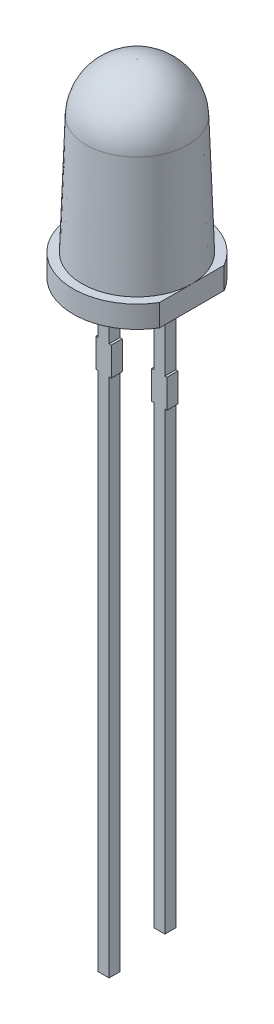
SolidWorks part; units mm, degrees
ref_plane "Front Plane" through (0, 0, 0) normal (0, 0, 1) x (1, 0, 0)
ref_plane "Top Plane" through (0, 0, 0) normal (0, 1, 0) x (1, 0, 0)
ref_plane "Right Plane" through (0, 0, 0) normal (1, 0, 0) x (0, 0, -1)
sketch "Sketch4" plane through (0, 0, 0) normal (0, 1, 0) x (1, 0, 0)
  line L0 (2.9743, 0) -> (-3.696, 0) construction
  line L2 (-1.52, 0.25) -> (-1.02, 0.25)
  line L3 (-1.52, 0.25) -> (-1.52, -0.25)
  line L4 (-1.52, -0.25) -> (-1.02, -0.25)
  line L5 (-1.02, 0.25) -> (-1.02, -0.25)
  line L6 (-1.52, 0.25) -> (-1.02, -0.25) construction
  line L7 (-1.52, -0.25) -> (-1.02, 0.25) construction
  line L8 (1.02, 0.25) -> (1.52, 0.25)
  line L9 (1.02, 0.25) -> (1.02, -0.25)
  line L10 (1.02, -0.25) -> (1.52, -0.25)
  line L11 (1.52, 0.25) -> (1.52, -0.25)
  line L12 (1.02, 0.25) -> (1.52, -0.25) construction
  line L13 (1.02, -0.25) -> (1.52, 0.25) construction
  point P3 (-1.27, 0)
  point P8 (1.27, 0)
  dimension "D1" = 0.5
  dimension "D2" = 0.5
  dimension "D3" = 0.5
  dimension "D4" = 0.5
  dimension "D5" = 1.27
  dimension "D6" = 1.27
extrude "Boss-Extrude3" add sketch "Sketch4" along normal blind 3.5 and the other way blind 25 separate body
sketch "Sketch5" plane through (0, 0, 0.25) normal (0, 0, 1) x (1, 0, 0)
  line L0 (-1.02, 3.3269) -> (-0.3288, 2.4555)
  line L2 (-1.02, -25) -> (-1.02, 3.5) construction
  line L3 (-0.3288, 2.4555) -> (-0.3288, 2.1844)
  line L4 (-0.3288, 2.1844) -> (-1.02, 2.1844)
  line L5 (-1.02, 2.1844) -> (-1.02, 3.3269)
  line L6 (1.02, 3.399) -> (-0.7949, 3.399)
  line L7 (1.02, -25) -> (1.02, 3.5) construction
  line L8 (-0.7949, 3.399) -> (0.1685, 2.1844)
  line L9 (0.1685, 2.1844) -> (1.02, 2.1844)
  line L10 (1.02, 2.1844) -> (1.02, 3.399)
extrude "Boss-Extrude4" add sketch "Sketch5" against normal blind 0.5
sketch "Sketch7" plane through (0, 3.399, 0) normal (0, 1, 0) x (1, 0, 0)
  line L0 (-0.538, 0) -> (0.9252, 0)
  arc A0 (-0.538, 0) -> (0.9252, 0) centre (0.1936, 0) ccw
revolve "Revolve1" add sketch "Sketch7" angle 180 about L0
sketch "Sketch8" plane through (0, 3.399, 0) normal (0, 1, 0) x (1, 0, 0)
  line L0 (-0.4407, 0) -> (0.8303, 0)
  arc A0 (-0.4407, 0) -> (0.8303, 0) centre (0.1948, 0.0036) ccw
revolve "Cut-Revolve1" cut sketch "Sketch8" angle 360 about L0
sketch "Sketch9" plane through (0, 3.5, 0) normal (0, 1, 0) x (1, 0, 0)
  circle A0 centre (-1.3038, 0) radius 0.02
ref_plane "Plane1" through (0, 2.9, 0) normal (0, 1, 0) x (1, 0, 0)
sketch "Sketch10" plane through (0, 2.9, 0) normal (0, 1, 0) x (1, 0, 0)
  line L1 (-0.1178, 0.3117) -> (0.4822, 0.3117)
  line L2 (-0.1178, 0.3117) -> (-0.1178, -0.2883)
  line L3 (-0.1178, -0.2883) -> (0.4822, -0.2883)
  line L4 (0.4822, 0.3117) -> (0.4822, -0.2883)
  line L5 (-0.1178, 0.3117) -> (0.4822, -0.2883) construction
  line L6 (-0.1178, -0.2883) -> (0.4822, 0.3117) construction
  arc A0 (0.8303, 0) -> (-0.4407, 0) centre (0.1948, -0.0036) ccw construction
  point P0 (0.1822, 0.0117)
  dimension "D1" = 0.6
  dimension "D2" = 0.6
extrude "Boss-Extrude5" add sketch "Sketch10" along normal blind 0.2
sketch "Sketch11" plane through (0, 3.1, 0) normal (0, 1, 0) x (1, 0, 0)
  line L1 (0.0731, 0.0871) -> (0.2767, 0.0871)
  line L2 (0.0731, 0.0871) -> (0.0731, -0.0871)
  line L3 (0.0731, -0.0871) -> (0.2767, -0.0871)
  line L4 (0.2767, 0.0871) -> (0.2767, -0.0871)
  line L5 (0.0731, 0.0871) -> (0.2767, -0.0871) construction
  line L6 (0.0731, -0.0871) -> (0.2767, 0.0871) construction
  point P0 (0.1749, 0)
extrude "Boss-Extrude6" add sketch "Sketch11" along normal blind 0.05
sketch3d "3DSketch1"
  spline S0 degree 3 poles (-1.3038, 3.5, 0) (-1.3325, 3.672, 0) (-0.9418, 3.891, 0) (-0.1244, 3.8563, 0) (0.1242, 3.692, 0) (0.2258, 3.5852, 0) (0.1729, 3.1438, 0) knots 0 0 0 0 0.135885 0.523149 0.614401 1 1 1 1
sweep "Sweep1" add profiles "Sketch9" path "3DSketch1"
fillet "Fillet2" radius 0.02 10 edges at (0.1749, 3.15, 0.0871) (0.0731, 3.15, 0) (0.1749, 3.15, -0.0871) (0.2767, 3.15, 0) (-1.3238, 3.5, 0) (0.178, 3.15, -0.0195) (0.2767, 3.1, 0) (0.1749, 3.1, -0.0871) (0.0731, 3.1, 0) (0.1749, 3.1, 0.0871)
sketch "Sketch1" plane through (0, 0, 0) normal (0, 1, 0) x (1, 0, 0)
  circle A0 centre (0, 0) radius 2.9
  dimension "D1" = 5.8
sketch "Sketch3" plane through (0, 0, 0) normal (0, 1, 0) x (1, 0, 0)
  line L1 (2.5, 3.0597) -> (3.9249, 3.0597)
  line L2 (2.5, 3.0597) -> (2.5, -2.9564)
  line L3 (2.5, -2.9564) -> (3.9249, -2.9564)
  line L4 (3.9249, 3.0597) -> (3.9249, -2.9564)
extrude "Boss-Extrude7" add sketch "Sketch1" along normal blind 1 separate body
extrude "Cut-Extrude3" cut sketch "Sketch3" along normal blind 1
sketch "Sketch12" plane through (0, 1, 0) normal (0, 1, 0) x (1, 0, 0)
  circle A0 centre (0, 0) radius 2.5
extrude "Boss-Extrude8" add sketch "Sketch12" along normal blind 7.6 draft 2 separate body
fillet "Fillet3" radius 2.3 1 edges at (0, 8.6, 2.2346)
sketch "Sketch13" plane through (0, -25, 0) normal (0, -1, 0) x (1, 0, 0)
  line L1 (-1.52, 0.25) -> (-1.02, 0.25)
  line L2 (-1.52, 0.25) -> (-1.52, -0.25)
  line L3 (-1.52, -0.25) -> (-1.02, -0.25)
  line L4 (-1.02, 0.25) -> (-1.02, -0.25)
extrude "Boss-Extrude9" add sketch "Sketch13" along normal blind 3
ref_plane "Plane2" through (0, -3, 0) normal (0, 1, 0) x (1, 0, 0)
sketch "Sketch14" plane through (0, -3, 0) normal (0, 1, 0) x (1, 0, 0)
  line L0 (-1.02, 0.25) -> (-0.3288, 0.25) construction
  line L1 (-1.6196, -0.25) -> (-0.9196, -0.25)
  line L2 (-1.6196, -0.25) -> (-1.6196, 0.25)
  line L3 (-1.6196, 0.25) -> (-0.9196, 0.25)
  line L4 (-0.9196, -0.25) -> (-0.9196, 0.25)
  line L5 (0.1685, -0.25) -> (1.02, -0.25) construction
  line L6 (0.9175, -0.25) -> (1.6175, -0.25)
  line L7 (0.9175, -0.25) -> (0.9175, 0.25)
  line L8 (0.9175, 0.25) -> (1.6175, 0.25)
  line L9 (1.6175, -0.25) -> (1.6175, 0.25)
  dimension "D1" = 0.7
  dimension "D2" = 0.7
extrude "Boss-Extrude10" add sketch "Sketch14" against normal blind 1.3
equation "\"D2@Sketch4\"=\"D1@Sketch4\""
equation "\"D3@Sketch4\"=\"D2@Sketch4\""
equation "\"D4@Sketch4\"=\"D1@Sketch4\""
equation "\"D2@Sketch10\"=\"D1@Sketch10\""
